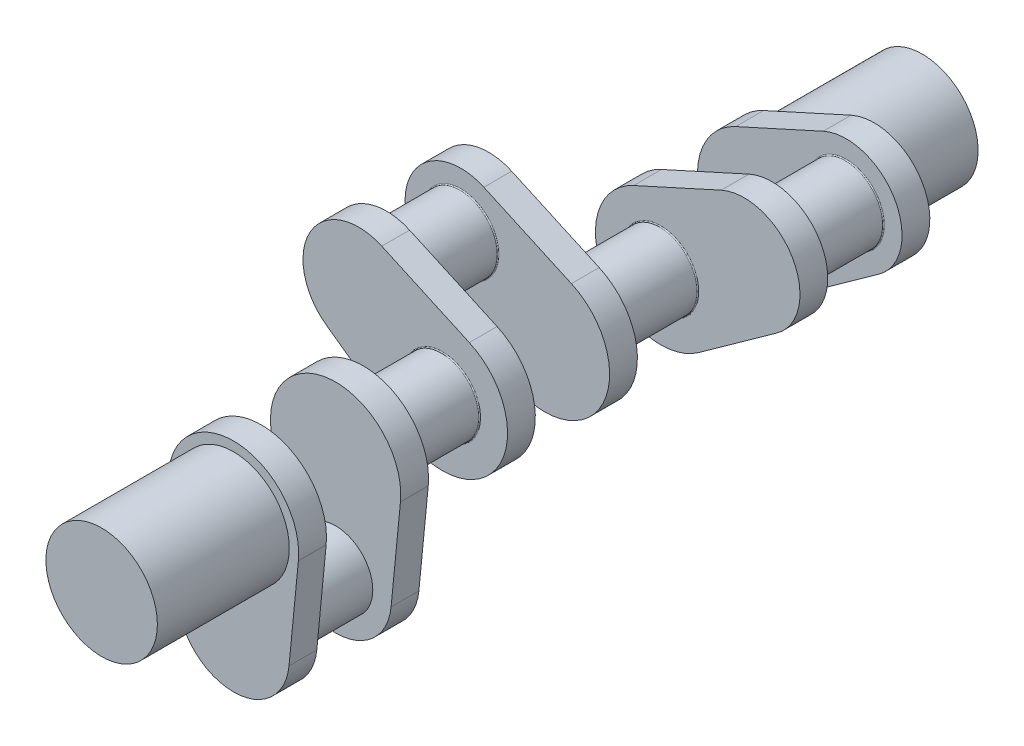
SolidWorks part; units mm, degrees
ref_plane "Front Plane" through (0, 0, 0) normal (0, 0, 1) x (1, 0, 0)
ref_plane "Top Plane" through (0, 0, 0) normal (0, 1, 0) x (1, 0, 0)
ref_plane "Right Plane" through (0, 0, 0) normal (1, 0, 0) x (0, 0, -1)
sketch "Sketch1" plane through (0, 0, 0) normal (0, 0, 1) x (1, 0, 0)
  line L0 (-44.3183, -4.337) -> (-37.9189, -69.7307)
  line L1 (0, 0) -> (0, -44.53) construction
  line L2 (44.3183, -4.337) -> (37.9189, -69.7307)
  arc A0 (44.3183, -4.337) -> (-44.3183, -4.337) centre (0, 0) ccw
  arc A1 (-37.9189, -69.7307) -> (37.9189, -69.7307) centre (0, -66.02) ccw
  dimension "D2" = 89.06
  dimension "D3" = 76.2
  dimension "D1" = 66.02
extrude "Boss-Extrude1" add sketch "Sketch1" against normal blind 19
sketch "Sketch2" plane through (0, 0, -19) normal (0, 0, -1) x (-1, 0, 0)
  circle A0 centre (0, -66.02) radius 25.4
  dimension "D1" = 50.8
extrude "Boss-Extrude2" add sketch "Sketch2" along normal blind 50.78
ref_plane "Plane1" through (0, 0, -44.39) normal (0, 0, -1) x (-1, 0, 0)
mirror "Mirror1" about plane through (0, 0, -44.39) normal (0, 0, -1) of "Boss-Extrude1"
sketch "Sketch3" plane through (0, 0, -88.78) normal (0, 0, -1) x (-1, 0, 0)
  circle A0 centre (0, 0) radius 25.4
  dimension "D1" = 50.8
extrude "Boss-Extrude3" add sketch "Sketch3" along normal blind 53.985
sketch "Sketch6" plane through (0, 0, -142.765) normal (0, 0, -1) x (-1, 0, 0)
  line L4 (25.9151, -36.2123) -> (79.348, 2.0267)
  line L5 (41.4292, 67.7041) -> (-18.4032, 40.5493)
  arc A4 (-18.4032, 40.5493) -> (25.9151, -36.2123) centre (0, 0) ccw
  arc A5 (79.348, 2.0267) -> (41.4292, 67.7041) centre (57.175, 33.01) ccw
extrude "Boss-Extrude5" add sketch "Sketch6" along normal blind 19
sketch "Sketch7" plane through (0, 0, -161.765) normal (0, 0, -1) x (-1, 0, 0)
  circle A0 centre (57.175, 33.01) radius 25.4
  dimension "D1" = 50.8
extrude "Boss-Extrude7" add sketch "Sketch7" along normal blind 50.78 contours A0
ref_plane "Plane3" through (0, 0, -187.155) normal (0, 0, -1) x (-1, 0, 0)
mirror "Mirror3" about plane through (0, 0, -187.155) normal (0, 0, -1) of "Boss-Extrude5"
sketch "Sketch8" plane through (0, 0, -231.545) normal (0, 0, -1) x (-1, 0, 0)
  circle A0 centre (0, 0) radius 25.4
  dimension "D1" = 50.8
extrude "Boss-Extrude8" add sketch "Sketch8" along normal blind 60.38
sketch "Sketch9" plane through (0, 0, -291.925) normal (0, 0, -1) x (-1, 0, 0)
  line L4 (18.4032, 40.5493) -> (-41.4292, 67.7041)
  line L5 (-79.348, 2.0267) -> (-25.9151, -36.2123)
  arc A4 (-25.9151, -36.2123) -> (18.4032, 40.5493) centre (0, 0) ccw
  arc A5 (-41.4292, 67.7041) -> (-79.348, 2.0267) centre (-57.175, 33.01) ccw
extrude "Boss-Extrude9" add sketch "Sketch9" along normal blind 19
sketch "Sketch10" plane through (0, 0, -310.925) normal (0, 0, -1) x (-1, 0, 0)
  circle A0 centre (-57.175, 33.01) radius 25.4
  dimension "D1" = 50.8
extrude "Boss-Extrude10" add sketch "Sketch10" along normal blind 50.78
ref_plane "Plane4" through (0, 0, -336.315) normal (0, 0, -1) x (-1, 0, 0)
mirror "Mirror4" about plane through (0, 0, -336.315) normal (0, 0, -1) of "Boss-Extrude9"
sketch "Sketch11" plane through (0, 0, -380.705) normal (0, 0, -1) x (-1, 0, 0)
  circle A0 centre (0, 0) radius 38.1
  dimension "D1" = 76.2
extrude "Boss-Extrude11" add sketch "Sketch11" along normal blind 90.17
sketch "Sketch12" plane through (0, 0, 0) normal (0, 0, 1) x (1, 0, 0)
  circle A0 centre (0, 0) radius 38.1
  dimension "D1" = 76.2
extrude "Boss-Extrude12" add sketch "Sketch12" along normal blind 90.17
fillet "Fillet1" radius 0.64 9 edges at (25.4, -66.02, -19) (31.775, 33.01, -310.925) (31.775, 33.01, -361.705) (25.4, 0, -231.545) (-25.4, 0, -291.925) (-82.575, 33.01, -161.765) (-82.575, 33.01, -212.545) (-25.4, 0, -88.78) (-25.4, 0, -142.765)
